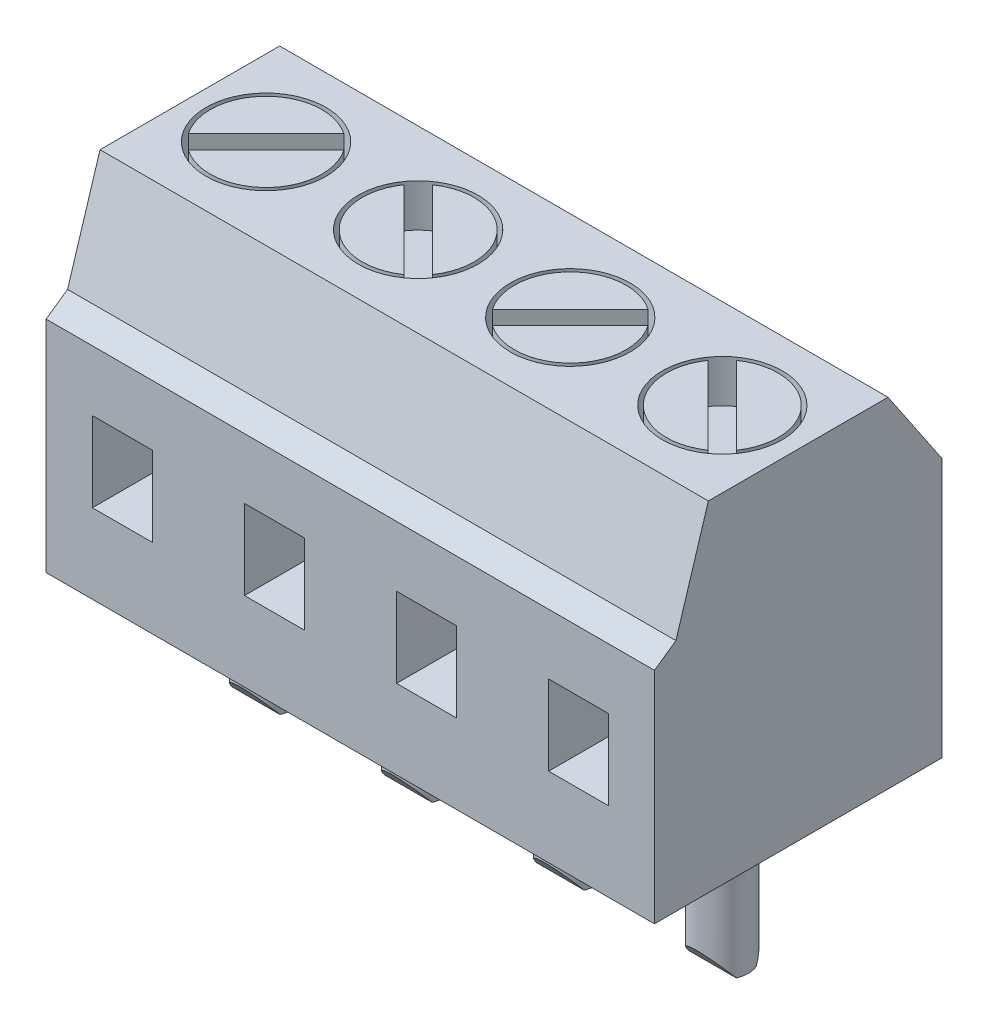
SolidWorks part; units mm, degrees
ref_plane "Alzado" through (0, 0, 0) normal (0, 0, 1) x (1, 0, 0)
ref_plane "Planta" through (0, 0, 0) normal (0, 1, 0) x (1, 0, 0)
ref_plane "Vista lateral" through (0, 0, 0) normal (1, 0, 0) x (0, 0, -1)
sketch "Sketch3" plane through (0, 0, 0) normal (0, 1, 0) x (1, 0, 0)
  line L0 (0, 0) -> (15.24, 0)
  line L1 (0, 0) -> (0, 7.2)
  line L2 (0, 7.2) -> (15.24, 7.2)
  line L3 (15.24, 0) -> (15.24, 7.2)
extrude "Boss-Extrude1" add sketch "Sketch3" along normal blind 8.5
sketch "Sketch4" plane through (0, 0, 0) normal (0, -1, 0) x (-1, 0, 0)
  circle A0 centre (-1.91, 3.6) radius 0.65
  circle A1 centre (-5.72, 3.6) radius 0.65
  circle A2 centre (-9.53, 3.6) radius 0.65
  circle A3 centre (-13.34, 3.6) radius 0.65
extrude "Boss-Extrude2" add sketch "Sketch4" along normal blind 3.5
sketch "Sketch5" plane through (0, 0, 0) normal (-1, 0, 0) x (0, 0, 1)
  line L1 (-2.95, -3) -> (-2.95, -3.5)
  line L5 (-4.25, 0) -> (-4.25, -3.5) construction
  line L6 (-2.95, -3.5) -> (-2.95, 0) construction
  line L7 (-2.95, -3) -> (-3.35, -3.5)
  line L8 (-4.25, -3) -> (-3.85, -3.5)
  line L9 (-2.95, -3.5) -> (-3.35, -3.5)
  line L10 (-4.25, -3) -> (-4.25, -3.5)
  line L11 (-4.25, -3.5) -> (-3.85, -3.5)
  dimension "D1" = 0.5
  dimension "D2" = 0.4
  dimension "D3" = 0.5
  dimension "D4" = 0.4
extrude "Cut-Extrude1" cut sketch "Sketch5" against normal up to surface (15.24 mm away) up to face at (15.24, 4.25, -3.6)
sketch "Sketch8" plane through (15.24, 0, 0) normal (1, 0, 0) x (0, 0, -1)
  line L1 (0, 8.5) -> (0, 0) construction
  line L2 (0, 5.5) -> (0.5373, 5.8762)
  line L4 (0.5373, 5.8762) -> (1.35, 8.5)
  line L6 (7.2, 8.5) -> (7.2, 0) construction
  line L7 (7.2, 6.5) -> (5.85, 8.5)
  line L8 (5.85, 8.5) -> (7.2, 8.5)
  line L9 (7.2, 8.5) -> (7.2, 6.5)
  line L10 (0, 5.5) -> (0, 8.5)
  line L11 (0, 8.5) -> (1.35, 8.5)
  dimension "D3" = 4.5
  dimension "D2" = 0.6559
  dimension "D4" = 2.7468
  dimension "D6" = 2.413
  dimension "D7" = 1.35
  dimension "D8" = 2
  dimension "D9" = 3
  dimension "D10" = 1.35
extrude "Cut-Extrude3" cut sketch "Sketch8" against normal up to surface (15.24 mm away) up to face at (0, 4.25, -3.6)
sketch "Sketch13" plane through (0, 0, 0) normal (0, 0, 1) x (1, 0, 0)
  line L0 (12.59, 1.9867) -> (14.09, 1.9867)
  line L1 (12.59, 1.9867) -> (12.59, 3.9867)
  line L2 (12.59, 3.9867) -> (14.09, 3.9867)
  line L3 (14.09, 3.9867) -> (14.09, 1.9867)
  line L7 (8.78, 1.9867) -> (10.28, 1.9867)
  line L8 (8.78, 1.9867) -> (8.78, 3.9867)
  line L9 (8.78, 3.9867) -> (10.28, 3.9867)
  line L10 (10.28, 1.9867) -> (10.28, 3.9867)
  line L14 (4.97, 1.9867) -> (6.47, 1.9867)
  line L15 (4.97, 1.9867) -> (4.97, 3.9867)
  line L16 (4.97, 3.9867) -> (6.47, 3.9867)
  line L17 (6.47, 1.9867) -> (6.47, 3.9867)
  line L20 (1.16, 1.9867) -> (2.66, 1.9867)
  line L21 (1.16, 1.9867) -> (1.16, 3.9867)
  line L22 (1.16, 3.9867) -> (2.66, 3.9867)
  line L23 (2.66, 1.9867) -> (2.66, 3.9867)
extrude "Cut-Extrude4" cut sketch "Sketch13" against normal blind 2 draft 6
sketch "Sketch14" plane through (0, 8.5, 0) normal (0, 1, 0) x (1, 0, 0)
  circle A0 centre (1.91, 3.6) radius 1.5
  circle A1 centre (5.72, 3.6) radius 1.5
  circle A2 centre (9.53, 3.6) radius 1.5
  circle A3 centre (13.34, 3.6) radius 1.5
  circle A4 centre (1.91, 3.6) radius 1.4
  circle A5 centre (5.72, 3.6) radius 1.4
  circle A6 centre (9.53, 3.6) radius 1.4
  circle A7 centre (13.34, 3.6) radius 1.4
extrude "Cut-Extrude5" cut sketch "Sketch14" against normal blind 2
sketch "Sketch15" plane through (0, 8.5, 0) normal (0, 1, 0) x (1, 0, 0)
  line L4 (1.1025, 2.439) -> (3.071, 4.4075)
  line L5 (8.7327, 2.4492) -> (10.6808, 4.3973)
  line L6 (6.8708, 2.8027) -> (4.9227, 4.7508)
  line L7 (14.4908, 2.8027) -> (12.5427, 4.7508)
  line L8 (0.749, 2.7925) -> (2.7175, 4.761)
  line L9 (8.3792, 2.8027) -> (10.3273, 4.7508)
  line L10 (6.5173, 2.4492) -> (4.5692, 4.3973)
  line L11 (14.1373, 2.4492) -> (12.1892, 4.3973)
  arc A0 (8.3792, 2.8027) -> (8.7327, 2.4492) centre (9.53, 3.6) ccw
  arc A1 (14.1373, 2.4492) -> (14.4908, 2.8027) centre (13.34, 3.6) ccw
  arc A2 (6.5173, 2.4492) -> (6.8708, 2.8027) centre (5.72, 3.6) ccw
  arc A3 (0.749, 2.7925) -> (1.1025, 2.439) centre (1.91, 3.6) ccw
  arc A4 (3.071, 4.4075) -> (2.7175, 4.761) centre (1.91, 3.6) ccw
  arc A5 (4.9227, 4.7508) -> (4.5692, 4.3973) centre (5.72, 3.6) ccw
  arc A6 (10.6808, 4.3973) -> (10.3273, 4.7508) centre (9.53, 3.6) ccw
  arc A7 (12.5427, 4.7508) -> (12.1892, 4.3973) centre (13.34, 3.6) ccw
  point P0 (0.4958, 2.1858)
  point P1 (3.3242, 5.0142)
  point P2 (8.1158, 2.1858)
  point P3 (10.9442, 5.0142)
  point P4 (7.1342, 2.1858)
  point P5 (4.3058, 5.0142)
  point P6 (14.7542, 2.1858)
  point P7 (11.9258, 5.0142)
  point P9 (0.6726, 2.009)
  point P10 (3.501, 4.8374)
  point P11 (8.2926, 2.009)
  point P12 (11.121, 4.8374)
  point P13 (7.311, 2.3626)
  point P14 (4.4826, 5.191)
  point P15 (14.931, 2.3626)
  point P16 (12.1026, 5.191)
  point P17 (0.319, 2.3626)
  point P18 (3.1474, 5.191)
  point P19 (7.939, 2.3626)
  point P20 (10.7674, 5.191)
  point P21 (6.9574, 2.009)
  point P22 (4.129, 4.8374)
  point P23 (14.5774, 2.009)
  point P24 (11.749, 4.8374)
extrude "Cut-Extrude6" cut sketch "Sketch15" against normal blind 1
